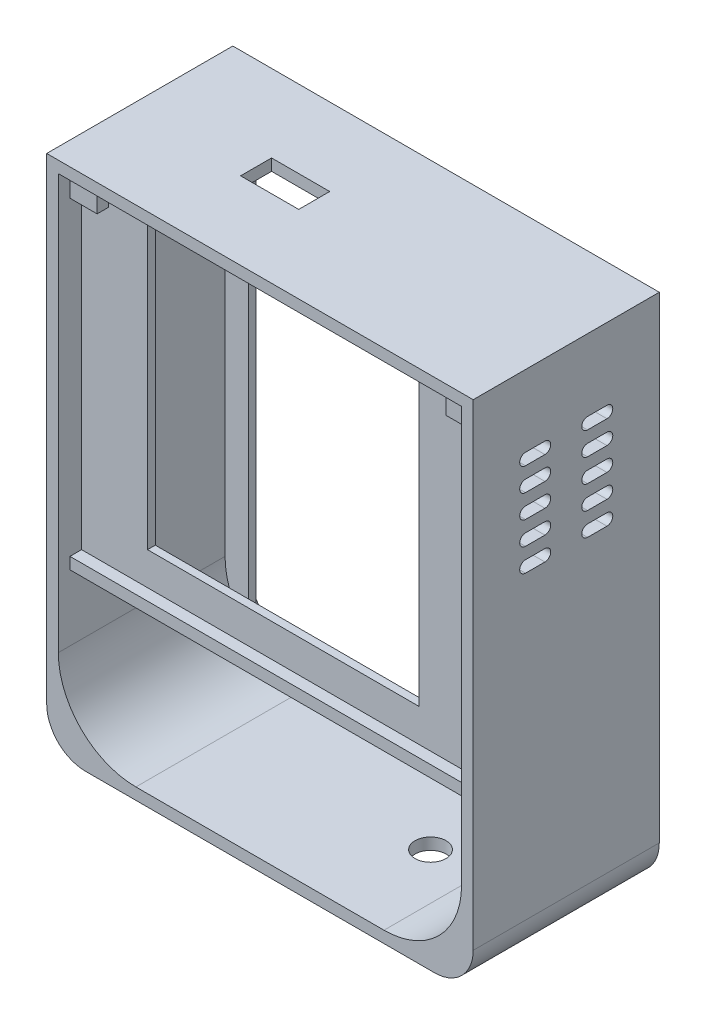
SolidWorks part; units mm, degrees
ref_plane "前视基准面" through (0, 0, 0) normal (0, 0, 1) x (1, 0, 0)
ref_plane "上视基准面" through (0, 0, 0) normal (0, 1, 0) x (1, 0, 0)
ref_plane "右视基准面" through (0, 0, 0) normal (1, 0, 0) x (0, 0, -1)
sketch "草图1" plane through (0, 0, 0) normal (0, 0, 1) x (1, 0, 0)
  line L1 (-55, 66.5) -> (55, 66.5)
  line L2 (-55, 66.5) -> (-55, -66.5)
  line L3 (-55, -66.5) -> (55, -66.5)
  line L4 (55, 66.5) -> (55, -66.5)
  line L5 (-55, 66.5) -> (55, -66.5) construction
  line L6 (-55, -66.5) -> (55, 66.5) construction
  point P0 (0, 0)
  dimension "D1" = 110
  dimension "D2" = 133
extrude "凸台-拉伸1" add sketch "草图1" along normal blind 48
sketch "草图2" plane through (0, 0, 48) normal (0, 0, 1) x (1, 0, 0)
  line L0 (-52, 63.5) -> (-52, -63.5)
  line L1 (-52, -63.5) -> (52, -63.5)
  line L2 (52, -63.5) -> (52, 63.5)
  line L3 (52, 63.5) -> (-52, 63.5)
  line L4 (-55, 66.5) -> (-55, -66.5) construction
  line L5 (55, -66.5) -> (55, 66.5) construction
  line L6 (-55, -66.5) -> (55, -66.5) construction
  line L7 (55, 66.5) -> (-55, 66.5) construction
  dimension "D1" = 3
  dimension "D2" = 3
  dimension "D3" = 3
  dimension "D4" = 3
extrude "切除-拉伸1" cut sketch "草图2" against normal blind 50
sketch "草图3" plane through (0, 63.5, 0) normal (0, -1, 0) x (1, 0, 0)
  line L13 (-52, 42) -> (-52, 40)
  line L14 (-52, 40) -> (52, 40)
  line L15 (52, 40) -> (52, 42)
  line L16 (52, 42) -> (-52, 42)
  line L17 (-55, 48) -> (55, 48) construction
  line L18 (-55, 48) -> (-55, 0) construction
  line L19 (55, 48) -> (55, 0) construction
  point P7 (-52, 41)
  dimension "D1" = 2
  dimension "D2" = 6
  dimension "D3" = 3
  dimension "D4" = 3
extrude "凸台-拉伸2" add sketch "草图3" along normal blind 90
sketch "草图4" plane through (0, 0, 42) normal (0, 0, 1) x (1, 0, 0)
  line L0 (-35, 55) -> (-35, -15)
  line L1 (-35, -15) -> (35, -15)
  line L2 (35, -15) -> (35, 55)
  line L3 (35, 55) -> (-35, 55)
  line L4 (-52, 63.5) -> (-52, -63.5) construction
  line L5 (52, -26.5) -> (52, 63.5) construction
  line L6 (52, 63.5) -> (-52, 63.5) construction
  dimension "D1" = 17
  dimension "D2" = 17
  dimension "D3" = 8.5
  dimension "D4" = 70
extrude "切除-拉伸2" cut sketch "草图4" against normal up to next
sketch "草图5" plane through (0, 0, 42) normal (0, 0, 1) x (1, 0, 0)
  line L0 (-52, -23.5) -> (-52, -26.5)
  line L1 (-52, -26.5) -> (-52, 63.5) construction
  line L2 (-52, -26.5) -> (52, -26.5)
  line L3 (52, -26.5) -> (52, -23.5)
  line L4 (52, -26.5) -> (52, 63.5) construction
  line L5 (52, -23.5) -> (-52, -23.5)
  dimension "D1" = 3
extrude "凸台-拉伸3" add sketch "草图5" along normal blind 3
sketch "草图6" plane through (0, 66.5, 0) normal (0, 1, 0) x (1, 0, 0)
  line L0 (-25, -20) -> (-25, -28)
  line L1 (-25, -28) -> (-10, -28)
  line L2 (-10, -28) -> (-10, -20)
  line L3 (-10, -20) -> (-25, -20)
  line L4 (55, 0) -> (-55, 0) construction
  line L5 (-55, -48) -> (-55, 0) construction
  dimension "D1" = 15
  dimension "D2" = 8
  dimension "D3" = 20
  dimension "D4" = 30
extrude "切除-拉伸3" cut sketch "草图6" against normal blind 10
sketch "草图8" plane through (0, 0, 42) normal (0, 0, 1) x (1, 0, 0)
  line L0 (-35, 55) -> (-35, 63.5)
  line L1 (52, 63.5) -> (-52, 63.5) construction
  line L2 (-35, 63.5) -> (35, 63.5)
  line L3 (35, 63.5) -> (35, 55)
  line L4 (35, 55) -> (-35, 55)
extrude "切除-拉伸4" cut sketch "草图8" against normal blind 2
sketch "草图9" plane through (52, 0, 0) normal (-1, 0, 0) x (0, 0, 1)
  line L6 (3, 63.5) -> (3, -63.5)
  line L7 (3, -63.5) -> (5, -63.5)
  line L8 (5, -63.5) -> (5, 63.5)
  line L9 (5, 63.5) -> (3, 63.5)
  line L10 (0, 66.5) -> (0, -66.5) construction
  line L11 (48, -66.5) -> (0, -66.5) construction
  line L12 (48, 66.5) -> (0, 66.5) construction
  dimension "D1" = 3
  dimension "D2" = 2
  dimension "D3" = 3
  dimension "D4" = 3
extrude "凸台-拉伸4" add sketch "草图9" along normal up to next
sketch "草图10" plane through (0, 0, 3) normal (0, 0, -1) x (-1, 0, 0)
  line L0 (-46, 57.5) -> (-46, -57.5)
  line L1 (-46, -57.5) -> (46, -57.5)
  line L2 (46, -57.5) -> (46, 57.5)
  line L3 (46, 57.5) -> (-46, 57.5)
  line L4 (-52, -63.5) -> (-52, 63.5) construction
  line L5 (52, 63.5) -> (-52, 63.5) construction
  line L6 (52, 63.5) -> (52, -63.5) construction
  line L7 (52, -63.5) -> (-52, -63.5) construction
  dimension "D1" = 6
  dimension "D2" = 6
  dimension "D3" = 6
  dimension "D4" = 6
extrude "切除-拉伸5" cut sketch "草图10" against normal blind 8
fillet "圆角10" radius 10 1 edges at (-55, -66.5, 24)
fillet "圆角11" radius 20 1 edges at (-52, -63.5, 1.5)
fillet "圆角12" radius 20 1 edges at (52, -63.5, 1.5)
fillet "圆角13" radius 10 1 edges at (55, -66.5, 24)
fillet "圆角14" radius 20 2 edges at (-52, 63.5, 1.5) (52, 63.5, 1.5)
fillet "圆角15" radius 20 1 edges at (52, -63.5, 26.5)
fillet "圆角16" radius 20 1 edges at (-52, -63.5, 26.5)
sketch "草图11" plane through (0, 0, 42) normal (0, 0, 1) x (1, 0, 0)
  line L0 (52, 63.5) -> (45, 63.5)
  line L1 (52, 63.5) -> (35, 63.5) construction
  line L2 (45, 63.5) -> (45, 56.5)
  line L3 (45, 56.5) -> (52, 56.5)
  line L4 (52, -23.5) -> (52, 63.5) construction
  line L5 (52, 56.5) -> (52, 63.5)
  line L6 (-52, 63.5) -> (-52, 56.5)
  line L7 (-52, 63.5) -> (-52, -43.5) construction
  line L8 (-52, 56.5) -> (-45, 56.5)
  line L9 (-45, 56.5) -> (-45, 63.5)
  line L10 (52, 63.5) -> (-52, 63.5) construction
  line L11 (-45, 63.5) -> (-52, 63.5)
  dimension "D1" = 7
  dimension "D2" = 7
  dimension "D3" = 7
  dimension "D4" = 7
extrude "凸台-拉伸5" add sketch "草图11" along normal blind 3
sketch "草图12" plane through (0, -66.5, 0) normal (0, -1, 0) x (1, 0, 0)
  line L0 (-45, 0) -> (45, 0) construction
  line L1 (-45, 48) -> (-45, 0) construction
  circle A0 centre (20, 24) radius 4
  dimension "D1" = 24
  dimension "D3" = 8
  dimension "D2" = 65
extrude "切除-拉伸6" cut sketch "草图12" against normal blind 3
sketch "草图13" plane through (52, 0, 0) normal (-1, 0, 0) x (0, 0, 1)
  line L0 (13.5, 46.5) -> (18.5, 46.5) construction
  line L1 (13.5, 48) -> (18.5, 48)
  line L2 (13.5, 45) -> (18.5, 45)
  line L3 (48, 66.5) -> (0, 66.5) construction
  line L6 (24, 66.5) -> (24, -26.6994) construction
  line L9 (34.5, 46.5) -> (29.5, 46.5) construction
  line L12 (34.5, 48) -> (29.5, 48)
  line L15 (34.5, 45) -> (29.5, 45)
  line L16 (13.5, 40.5) -> (18.5, 40.5) construction
  line L17 (13.5, 42) -> (18.5, 42)
  line L18 (13.5, 39) -> (18.5, 39)
  line L19 (13.5, 34.5) -> (18.5, 34.5) construction
  line L20 (13.5, 36) -> (18.5, 36)
  line L21 (13.5, 33) -> (18.5, 33)
  line L22 (13.5, 28.5) -> (18.5, 28.5) construction
  line L23 (13.5, 30) -> (18.5, 30)
  line L24 (13.5, 27) -> (18.5, 27)
  line L25 (13.5, 22.5) -> (18.5, 22.5) construction
  line L26 (13.5, 24) -> (18.5, 24)
  line L27 (13.5, 21) -> (18.5, 21)
  line L28 (34.5, 22.5) -> (29.5, 22.5) construction
  line L29 (34.5, 24) -> (29.5, 24)
  line L30 (34.5, 21) -> (29.5, 21)
  line L31 (34.5, 28.5) -> (29.5, 28.5) construction
  line L32 (34.5, 30) -> (29.5, 30)
  line L33 (34.5, 27) -> (29.5, 27)
  line L34 (34.5, 34.5) -> (29.5, 34.5) construction
  line L35 (34.5, 36) -> (29.5, 36)
  line L36 (34.5, 33) -> (29.5, 33)
  line L37 (34.5, 40.5) -> (29.5, 40.5) construction
  line L38 (34.5, 42) -> (29.5, 42)
  line L39 (34.5, 39) -> (29.5, 39)
  arc A0 (13.5, 48) -> (13.5, 45) centre (13.5, 46.5) ccw
  arc A1 (18.5, 45) -> (18.5, 48) centre (18.5, 46.5) ccw
  arc A20 (34.5, 48) -> (34.5, 45) centre (34.5, 46.5) cw
  arc A21 (29.5, 45) -> (29.5, 48) centre (29.5, 46.5) cw
  arc A22 (13.5, 42) -> (13.5, 39) centre (13.5, 40.5) ccw
  arc A23 (18.5, 39) -> (18.5, 42) centre (18.5, 40.5) ccw
  arc A24 (13.5, 36) -> (13.5, 33) centre (13.5, 34.5) ccw
  arc A25 (18.5, 33) -> (18.5, 36) centre (18.5, 34.5) ccw
  arc A26 (13.5, 30) -> (13.5, 27) centre (13.5, 28.5) ccw
  arc A27 (18.5, 27) -> (18.5, 30) centre (18.5, 28.5) ccw
  arc A28 (13.5, 24) -> (13.5, 21) centre (13.5, 22.5) ccw
  arc A29 (18.5, 21) -> (18.5, 24) centre (18.5, 22.5) ccw
  arc A30 (34.5, 24) -> (34.5, 21) centre (34.5, 22.5) cw
  arc A31 (29.5, 21) -> (29.5, 24) centre (29.5, 22.5) cw
  arc A32 (34.5, 30) -> (34.5, 27) centre (34.5, 28.5) cw
  arc A33 (29.5, 27) -> (29.5, 30) centre (29.5, 28.5) cw
  arc A34 (34.5, 36) -> (34.5, 33) centre (34.5, 34.5) cw
  arc A35 (29.5, 33) -> (29.5, 36) centre (29.5, 34.5) cw
  arc A36 (34.5, 42) -> (34.5, 39) centre (34.5, 40.5) cw
  arc A37 (29.5, 39) -> (29.5, 42) centre (29.5, 40.5) cw
  point P2 (16, 46.5)
  point P7 (24, 66.5)
  point P15 (32, 46.5)
  point P23 (16, 40.5)
  point P30 (16, 34.5)
  point P37 (16, 28.5)
  point P44 (16, 22.5)
  point P49 (32, 22.5)
  point P56 (32, 28.5)
  point P63 (32, 34.5)
  point P70 (32, 40.5)
  dimension "D2" = 1.5
  dimension "D1" = 5
  dimension "D3" = 8
  dimension "D4" = 20
  dimension "D6" = 6
  dimension "D5" = 5
extrude "切除-拉伸7" cut sketch "草图13" against normal blind 3
